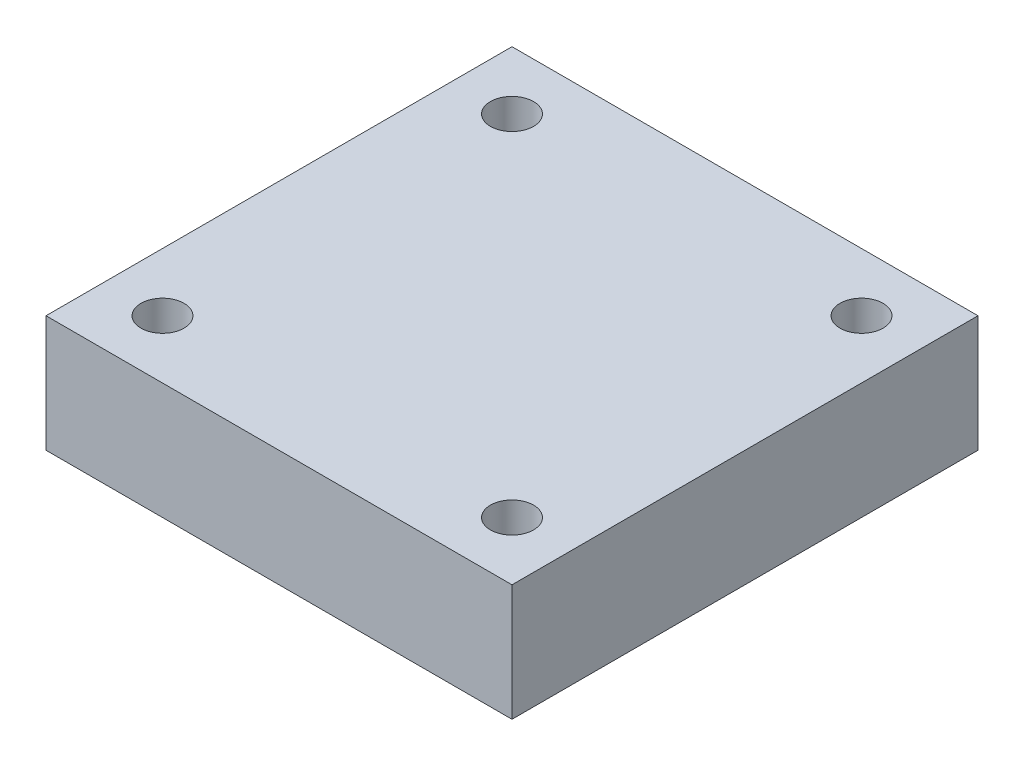
SolidWorks part; units mm, degrees
ref_plane "Front Plane" through (0, 0, 0) normal (0, 0, 1) x (1, 0, 0)
ref_plane "Top Plane" through (0, 0, 0) normal (0, 1, 0) x (1, 0, 0)
ref_plane "Right Plane" through (0, 0, 0) normal (1, 0, 0) x (0, 0, -1)
sketch "Sketch1" plane through (0, 0, 0) normal (0, 1, 0) x (1, 0, 0)
  line L0 (0, 0) -> (20, 0) construction
  line L1 (-20, -20) -> (20, -20)
  line L2 (-20, -20) -> (-20, 20)
  line L3 (-20, 20) -> (20, 20)
  line L4 (20, -20) -> (20, 20)
  line L5 (-20, -20) -> (20, 20) construction
  line L6 (-20, 20) -> (20, -20) construction
  circle A0 centre (-15, 15) radius 1.85
  circle A1 centre (15, -15) radius 1.85
  circle A2 centre (15, 15) radius 1.85
  circle A3 centre (-15, -15) radius 1.85
  point P0 (0, 0)
  dimension "D4" = 3.7
  dimension "D1" = 40
  dimension "D2" = 40
  dimension "D3" = 5
extrude "Boss-Extrude1" add sketch "Sketch1" along normal blind 10
